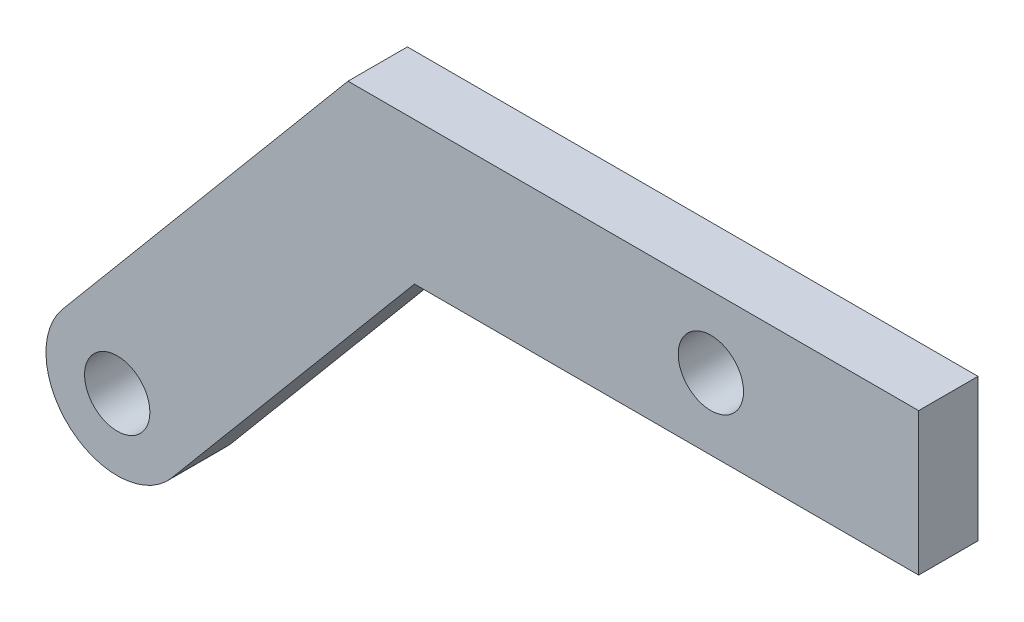
SolidWorks part; units mm, degrees
ref_plane "Front Plane" through (0, 0, 0) normal (0, 0, 1) x (1, 0, 0)
ref_plane "Top Plane" through (0, 0, 0) normal (0, 1, 0) x (1, 0, 0)
ref_plane "Right Plane" through (0, 0, 0) normal (1, 0, 0) x (0, 0, -1)
sketch "Sketch1" plane through (0, 0, 0) normal (0, 0, 1) x (1, 0, 0)
  line L2 (-9.1925, 7.7135) -> (38.8766, 65)
  line L3 (38.8766, 65) -> (135, 65)
  line L4 (135, 65) -> (135, 41)
  line L5 (135, 41) -> (50.068, 41)
  line L6 (50.068, 41) -> (9.1925, -7.7135)
  line L7 (0, 0) -> (110.8473, 0) construction
  circle A0 centre (0, 0) radius 5.5
  arc A1 (-9.1925, 7.7135) -> (9.1925, -7.7135) centre (0, 0) ccw
  circle A2 centre (100, 53) radius 5.5
  point P8 (0, 0)
  point P12 (135, 53)
  dimension "D1" = 11
  dimension "D2" = 24
  dimension "D8" = 11
  dimension "D3" = 50
  dimension "D4" = 24
  dimension "D5" = 65
  dimension "D6" = 135
  dimension "D7" = 35
extrude "Boss-Extrude1" add sketch "Sketch1" along normal blind 10
